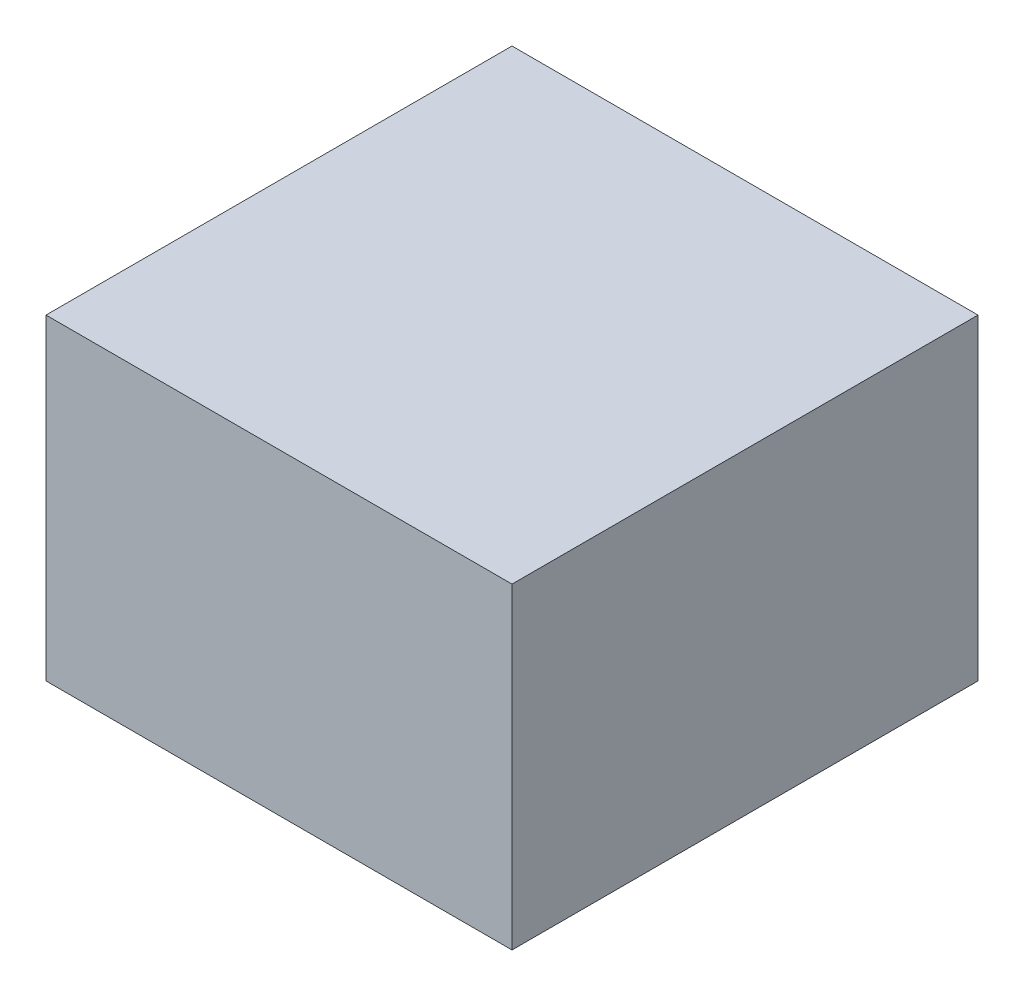
SolidWorks part; units mm, degrees
material "1060 Alloy"
ref_plane "Front Plane" through (0, 0, 0) normal (0, 0, 1) x (1, 0, 0)
ref_plane "Top Plane" through (0, 0, 0) normal (0, 1, 0) x (1, 0, 0)
ref_plane "Right Plane" through (0, 0, 0) normal (1, 0, 0) x (0, 0, -1)
sketch "Sketch1" plane through (0, 0, 0) normal (0, 1, 0) x (1, 0, 0)
  line L0 (0, 0) -> (50, 0)
  line L1 (50, 0) -> (50, 100)
  line L2 (50, 100) -> (-50, 100)
  line L3 (-50, 100) -> (-50, 0)
  line L4 (-50, 0) -> (0, 0)
  line L5 (50, 0) -> (100, 0)
  line L6 (100, 0) -> (150, 0)
  line L7 (150, 0) -> (150, 100)
  line L8 (150, 100) -> (50, 100)
  line L9 (50, 100) -> (50, 0)
  line L10 (150, 0) -> (200, 0)
  line L11 (200, 0) -> (250, 0)
  line L12 (250, 0) -> (250, 100)
  line L13 (250, 100) -> (150, 100)
  line L14 (150, 100) -> (150, 0)
  line L15 (250, 0) -> (300, 0)
  line L16 (300, 0) -> (350, 0)
  line L17 (350, 0) -> (350, 100)
  line L18 (350, 100) -> (250, 100)
  line L19 (250, 100) -> (250, 0)
  line L20 (350, 0) -> (400, 0)
  line L21 (400, 0) -> (450, 0)
  line L22 (450, 0) -> (450, 100)
  line L23 (450, 100) -> (350, 100)
  line L24 (350, 100) -> (350, 0)
  line L25 (50, 100) -> (100, 100)
  line L26 (100, 100) -> (150, 100)
  line L27 (150, 100) -> (150, 200)
  line L28 (150, 200) -> (50, 200)
  line L29 (50, 200) -> (50, 100)
  line L30 (150, 100) -> (200, 100)
  line L31 (200, 100) -> (250, 100)
  line L32 (250, 100) -> (250, 200)
  line L33 (250, 200) -> (150, 200)
  line L34 (150, 200) -> (150, 100)
  line L35 (250, 100) -> (300, 100)
  line L36 (300, 100) -> (350, 100)
  line L37 (350, 100) -> (350, 200)
  line L38 (350, 200) -> (250, 200)
  line L39 (250, 200) -> (250, 100)
  line L40 (350, 100) -> (400, 100)
  line L41 (400, 100) -> (450, 100)
  line L42 (450, 100) -> (450, 200)
  line L43 (450, 200) -> (350, 200)
  line L44 (350, 200) -> (350, 100)
  line L45 (50, 200) -> (100, 200)
  line L46 (100, 200) -> (150, 200)
  line L47 (150, 200) -> (150, 300)
  line L48 (150, 300) -> (50, 300)
  line L49 (50, 300) -> (50, 200)
  line L50 (150, 200) -> (200, 200)
  line L51 (200, 200) -> (250, 200)
  line L52 (250, 200) -> (250, 300)
  line L53 (250, 300) -> (150, 300)
  line L54 (150, 300) -> (150, 200)
  line L55 (250, 200) -> (300, 200)
  line L56 (300, 200) -> (350, 200)
  line L57 (350, 200) -> (350, 300)
  line L58 (350, 300) -> (250, 300)
  line L59 (250, 300) -> (250, 200)
  line L60 (350, 200) -> (400, 200)
  line L61 (400, 200) -> (450, 200)
  line L62 (450, 200) -> (450, 300)
  line L63 (450, 300) -> (350, 300)
  line L64 (350, 300) -> (350, 200)
  line L65 (50, 300) -> (100, 300)
  line L66 (100, 300) -> (150, 300)
  line L67 (150, 300) -> (150, 400)
  line L68 (150, 400) -> (50, 400)
  line L69 (50, 400) -> (50, 300)
  line L70 (150, 300) -> (200, 300)
  line L71 (200, 300) -> (250, 300)
  line L72 (250, 300) -> (250, 400)
  line L73 (250, 400) -> (150, 400)
  line L74 (150, 400) -> (150, 300)
  line L75 (250, 300) -> (300, 300)
  line L76 (300, 300) -> (350, 300)
  line L77 (350, 300) -> (350, 400)
  line L78 (350, 400) -> (250, 400)
  line L79 (250, 400) -> (250, 300)
  line L80 (350, 300) -> (400, 300)
  line L81 (400, 300) -> (450, 300)
  line L82 (450, 300) -> (450, 400)
  line L83 (450, 400) -> (350, 400)
  line L84 (350, 400) -> (350, 300)
  line L85 (50, 400) -> (100, 400)
  line L86 (100, 400) -> (150, 400)
  line L87 (150, 400) -> (150, 500)
  line L88 (150, 500) -> (50, 500)
  line L89 (50, 500) -> (50, 400)
  line L90 (150, 400) -> (200, 400)
  line L91 (200, 400) -> (250, 400)
  line L92 (250, 400) -> (250, 500)
  line L93 (250, 500) -> (150, 500)
  line L94 (150, 500) -> (150, 400)
  line L95 (250, 400) -> (300, 400)
  line L96 (300, 400) -> (350, 400)
  line L97 (350, 400) -> (350, 500)
  line L98 (350, 500) -> (250, 500)
  line L99 (250, 500) -> (250, 400)
  line L100 (350, 400) -> (400, 400)
  line L101 (400, 400) -> (450, 400)
  line L102 (450, 400) -> (450, 500)
  line L103 (450, 500) -> (350, 500)
  line L104 (350, 500) -> (350, 400)
  line L105 (-50, 100) -> (0, 100)
  line L106 (0, 100) -> (50, 100)
  line L107 (50, 100) -> (50, 200)
  line L108 (50, 200) -> (-50, 200)
  line L109 (-50, 200) -> (-50, 100)
  line L110 (-50, 200) -> (0, 200)
  line L111 (0, 200) -> (50, 200)
  line L112 (50, 200) -> (50, 300)
  line L113 (50, 300) -> (-50, 300)
  line L114 (-50, 300) -> (-50, 200)
  line L115 (-50, 300) -> (0, 300)
  line L116 (0, 300) -> (50, 300)
  line L117 (50, 300) -> (50, 400)
  line L118 (50, 400) -> (-50, 400)
  line L119 (-50, 400) -> (-50, 300)
  line L120 (-50, 400) -> (0, 400)
  line L121 (0, 400) -> (50, 400)
  line L122 (50, 400) -> (50, 500)
  line L123 (50, 500) -> (-50, 500)
  line L124 (-50, 500) -> (-50, 400)
  dimension "D1" = 5
  dimension "D2" = 5
extrude "Boss-Extrude1" add sketch "Sketch1" along normal blind 340 contours L123 L124 L118 L89 | L88 L89 L68 L87 | L92 L93 L87 L73 | L102 L103 L97 L83 | L97 L98 L92 L78 | L77 L78 L72 L58 | L68 L69 L48 L67 | L72 L73 L67 L53 | L118 L119 L113 L69 | L113 L114 L108 L49 | L52 L53 L47 L33 | L57 L58 L52 L38 | L62 L63 L57 L43 | L82 L83 L77 L63 | L42 L43 L37 L23 | L37 L38 L32 L18 | L32 L33 L27 L13 | L108 L109 L2 L29 | L3 L4 L0 L1 L2 | L7 L8 L1 L5 L6 | L12 L13 L7 L10 L11 | L17 L18 L12 L15 L16 | L22 L23 L17 L20 L21 | L48 L49 L28 L47
sketch "Sketch2" plane through (0, 0, 0) normal (0, -1, 0) x (-1, 0, 0)
  line L0 (-450, 500) -> (-450, 400)
  line L1 (-450, 0) -> (-450, 500) construction
  line L3 (-350, 400) -> (-350, 500)
  line L4 (-450, 500) -> (50, 500) construction
  line L5 (-350, 500) -> (-450, 500)
  line L6 (-450, 500) -> (-350, 400) construction
  line L7 (-350, 500) -> (-450, 400) construction
  circle A0 centre (-400, 450) radius 31
  circle A1 centre (-300, 450) radius 31
  circle A2 centre (-200, 450) radius 31
  circle A3 centre (-100, 450) radius 31
  circle A4 centre (0, 450) radius 31
  circle A5 centre (-300, 350) radius 31
  circle A6 centre (-200, 350) radius 31
  circle A7 centre (-100, 350) radius 31
  circle A8 centre (0, 350) radius 31
  circle A9 centre (-300, 250) radius 31
  circle A10 centre (-200, 250) radius 31
  circle A11 centre (-100, 250) radius 31
  circle A12 centre (0, 250) radius 31
  circle A13 centre (-300, 150) radius 31
  circle A14 centre (-200, 150) radius 31
  circle A15 centre (-100, 150) radius 31
  circle A16 centre (0, 150) radius 31
  circle A17 centre (-300, 50) radius 31
  circle A18 centre (-200, 50) radius 31
  circle A19 centre (-100, 50) radius 31
  circle A20 centre (0, 50) radius 31
  circle A21 centre (-400, 350) radius 31
  circle A22 centre (-400, 250) radius 31
  circle A23 centre (-400, 150) radius 31
  circle A24 centre (-400, 50) radius 31
  point P11 (0, 0)
  dimension "D1" = 5
  dimension "D2" = 5
extrude "Cut-Extrude1" cut sketch "Sketch2" against normal blind 330 contours A4 | A8 | A12 | A20 | A3 | A7 | A11 | A15 | A19 | A2 | A6 | A10 | A14 | A18 | A1 | A5 | A9 | A13 | A17 | A0 | A21 | A22 | A23 | A24 | A16
sketch "Sketch3" plane through (0, 0, 0) normal (0, -1, 0) x (-1, 0, 0)
  circle A0 centre (-400, 450) radius 40
  circle A1 centre (-300, 450) radius 40
  circle A2 centre (-200, 450) radius 40
  circle A3 centre (-100, 450) radius 40
  circle A4 centre (0, 450) radius 40
  circle A5 centre (-300, 350) radius 40
  circle A6 centre (-200, 350) radius 40
  circle A7 centre (-100, 350) radius 40
  circle A8 centre (0, 350) radius 40
  circle A9 centre (-300, 250) radius 40
  circle A10 centre (-200, 250) radius 40
  circle A11 centre (-100, 250) radius 40
  circle A12 centre (0, 250) radius 40
  circle A13 centre (-300, 150) radius 40
  circle A14 centre (-200, 150) radius 40
  circle A15 centre (-100, 150) radius 40
  circle A16 centre (0, 150) radius 40
  circle A17 centre (-300, 50) radius 40
  circle A18 centre (-200, 50) radius 40
  circle A19 centre (-100, 50) radius 40
  circle A20 centre (0, 50) radius 40
  circle A21 centre (-400, 350) radius 40
  circle A22 centre (-400, 250) radius 40
  circle A23 centre (-400, 150) radius 40
  circle A24 centre (-400, 50) radius 40
  dimension "D1" = 5
  dimension "D2" = 5
extrude "Cut-Extrude3" cut sketch "Sketch3" against normal blind 10
